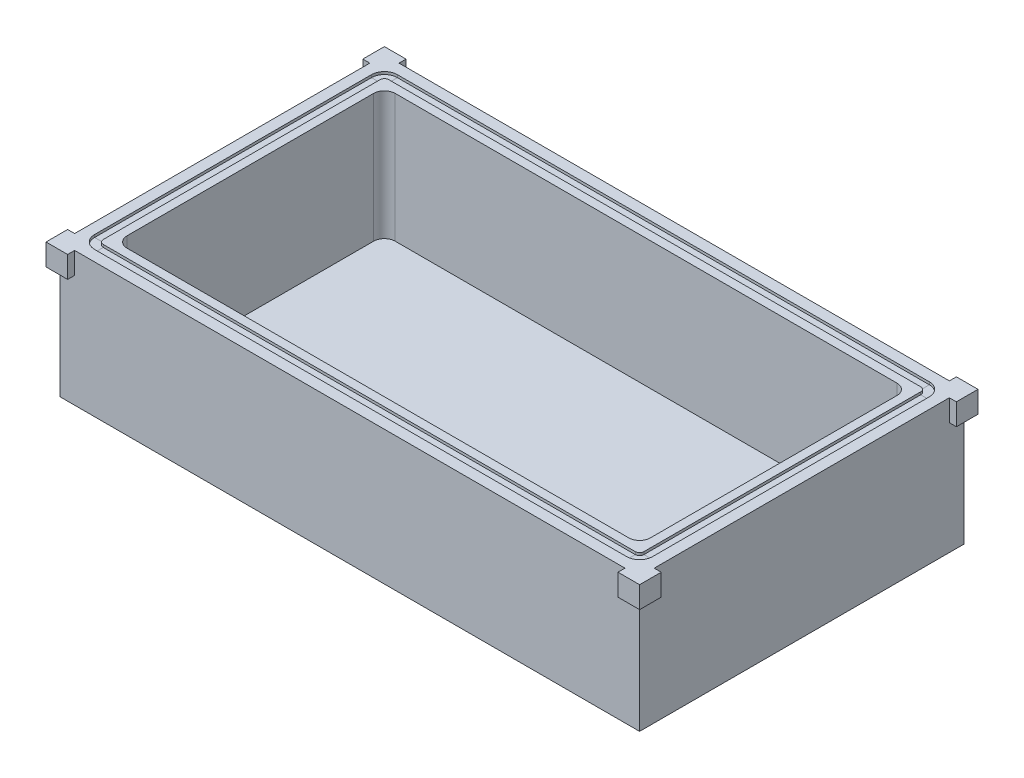
SolidWorks part; units mm, degrees
ref_plane "Front Plane" through (0, 0, 0) normal (0, 0, 1) x (1, 0, 0)
ref_plane "Top Plane" through (0, 0, 0) normal (0, 1, 0) x (1, 0, 0)
ref_plane "Right Plane" through (0, 0, 0) normal (1, 0, 0) x (0, 0, -1)
sketch "Sketch1" plane through (0, 0, 0) normal (0, 1, 0) x (1, 0, 0)
  line L0 (-85.09, -47.625) -> (-85.09, 47.625)
  line L5 (-85.09, -47.625) -> (85.09, -47.625)
  line L6 (-85.09, 47.625) -> (85.09, 47.625)
  line L7 (85.09, -47.625) -> (85.09, 47.625)
  line L8 (-85.09, -47.625) -> (85.09, 47.625) construction
  line L9 (-85.09, 47.625) -> (85.09, -47.625) construction
  point P0 (0, 0)
  dimension "D1" = 170.18
  dimension "D2" = 95.25
extrude "Boss-Extrude1" add sketch "Sketch1" along normal blind 39.37
sketch "Sketch2" plane through (0, 39.37, 0) normal (0, 1, 0) x (1, 0, 0)
  line L0 (-76.835, -39.37) -> (-76.835, 39.37)
  line L1 (-76.835, -39.37) -> (76.835, -39.37)
  line L2 (-76.835, 39.37) -> (76.835, 39.37)
  line L3 (76.835, -39.37) -> (76.835, 39.37)
  line L4 (-76.835, -39.37) -> (76.835, 39.37) construction
  line L5 (-76.835, 39.37) -> (76.835, -39.37) construction
  point P1 (0, 0)
  dimension "D1" = 153.67
  dimension "D2" = 78.74
extrude "Cut-Extrude1" cut sketch "Sketch2" against normal blind 37.592
sketch "Sketch3" plane through (0, 39.37, 0) normal (0, 1, 0) x (1, 0, 0)
  line L30 (-80.645, -43.18) -> (80.645, -43.18)
  line L31 (80.645, -43.18) -> (80.645, 43.18)
  line L32 (80.645, 43.18) -> (-80.645, 43.18)
  line L33 (-80.645, 43.18) -> (-80.645, -43.18)
  line L34 (-78.105, -43.18) -> (78.105, -43.18)
  line L35 (80.645, -40.64) -> (80.645, 40.64)
  line L36 (78.105, 43.18) -> (-78.105, 43.18)
  line L37 (-80.645, 40.64) -> (-80.645, -40.64)
  arc A0 (80.645, 40.64) -> (78.105, 43.18) centre (78.105, 40.64) ccw
  arc A1 (78.105, -43.18) -> (80.645, -40.64) centre (78.105, -40.64) ccw
  arc A2 (-80.645, -40.64) -> (-78.105, -43.18) centre (-78.105, -40.64) ccw
  arc A3 (-80.645, 40.64) -> (-78.105, 43.18) centre (-78.105, 40.64) cw
  dimension "D2" = 2.54
  dimension "D1" = 3.81
ref_plane "Plane1" through (-80.645, 39.37, 40.64) normal (0, 0, 1) x (1, 0, 0)
sketch "Sketch4" plane through (-80.645, 39.37, 40.64) normal (0, 0, 1) x (1, 0, 0)
  line L2 (1.27, 0.762) -> (-1.27, 0.762)
  line L3 (1.27, 0.762) -> (1.27, -0.762)
  line L4 (-1.27, 0.762) -> (-1.27, -0.762)
  line L5 (1.27, -0.762) -> (-1.27, -0.762)
  line L6 (1.27, 0.762) -> (-1.27, -0.762) construction
  line L7 (-1.27, 0.762) -> (1.27, -0.762) construction
  line L8 (2.54, 0) -> (0, 0) construction
  line L9 (-4.445, 0) -> (165.735, 0) construction
  point P1 (0, 0)
  dimension "D1" = 2.54
  dimension "D2" = 1.524
sweep "Cut-Sweep1" cut profiles "Sketch4" path "Sketch3"
fillet "Fillet1" radius 3.175 4 edges at (76.835, 20.574, 39.37) (-76.835, 20.574, 39.37) (-76.835, 20.574, -39.37) (76.835, 20.574, -39.37)
sketch "Sketch5" plane through (0, 39.37, 0) normal (0, 1, 0) x (1, 0, 0)
  line L0 (0, 0) -> (0, 50000) construction
  line L1 (-80.7991, 43.3341) -> (-87.1491, 43.3341)
  line L2 (-80.7991, 43.3341) -> (-80.7991, 49.6841)
  line L3 (-80.7991, 49.6841) -> (-87.1491, 49.6841)
  line L4 (-87.1491, 43.3341) -> (-87.1491, 49.6841)
  line L5 (0, 0) -> (-50000, 0) construction
  line L6 (87.1491, 43.3341) -> (87.1491, 49.6841)
  line L7 (80.7991, 49.6841) -> (87.1491, 49.6841)
  line L8 (80.7991, 43.3341) -> (80.7991, 49.6841)
  line L9 (80.7991, 43.3341) -> (87.1491, 43.3341)
  line L10 (80.7991, -43.3341) -> (87.1491, -43.3341)
  line L11 (80.7991, -43.3341) -> (80.7991, -49.6841)
  line L12 (80.7991, -49.6841) -> (87.1491, -49.6841)
  line L13 (87.1491, -43.3341) -> (87.1491, -49.6841)
  line L14 (-87.1491, -43.3341) -> (-87.1491, -49.6841)
  line L15 (-80.7991, -49.6841) -> (-87.1491, -49.6841)
  line L16 (-80.7991, -43.3341) -> (-80.7991, -49.6841)
  line L17 (-80.7991, -43.3341) -> (-87.1491, -43.3341)
  arc A0 (-78.105, 44.45) -> (-81.915, 40.64) centre (-78.105, 40.64) ccw construction
  dimension "D1" = 6.35
extrude "Boss-Extrude2" add sketch "Sketch5" against normal blind 6.35
